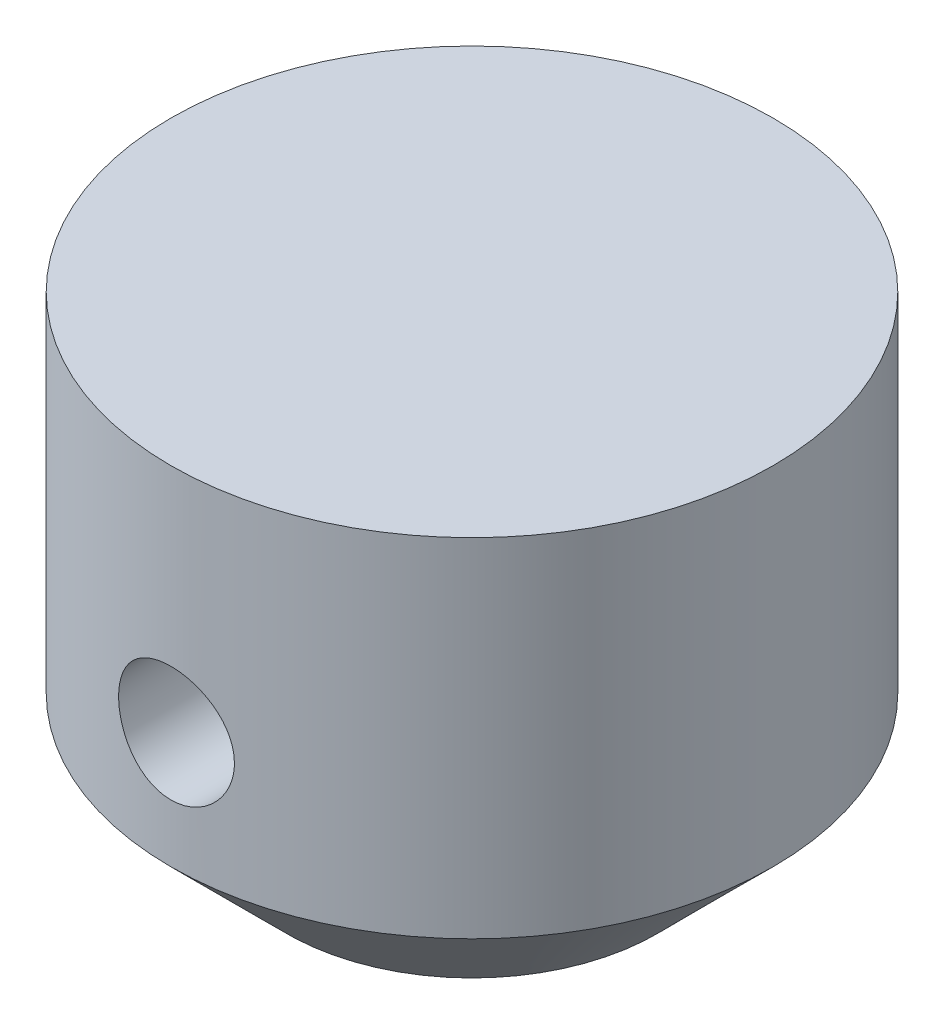
SolidWorks part; units mm, degrees
material "AISI 304"
ref_plane "Alzado" through (0, 0, 0) normal (0, 0, 1) x (1, 0, 0)
ref_plane "Planta" through (0, 0, 0) normal (0, 1, 0) x (1, 0, 0)
ref_plane "Vista lateral" through (0, 0, 0) normal (1, 0, 0) x (0, 0, -1)
sketch "Sketch1" plane through (0, 0, 0) normal (0, 0, 1) x (1, 0, 0)
  line L0 (0, -32) -> (2.6, -32)
  line L1 (2.6, -32) -> (2.6, -35)
  line L2 (2.6, -35) -> (1.6, -36)
  line L3 (1.6, -36) -> (0, -36)
  line L4 (0, -36) -> (0, -32)
  line L5 (0, -40) -> (0, -28) construction
revolve "Cubo_salida" add sketch "Sketch1" angle 360 about L5
sketch "Sketch2" plane through (0, 0, 0) normal (0, 0, 1) x (1, 0, 0)
  circle A0 centre (0, -34) radius 0.5
extrude "Paso_cuerda" cut sketch "Sketch2" against normal mid plane 2000
